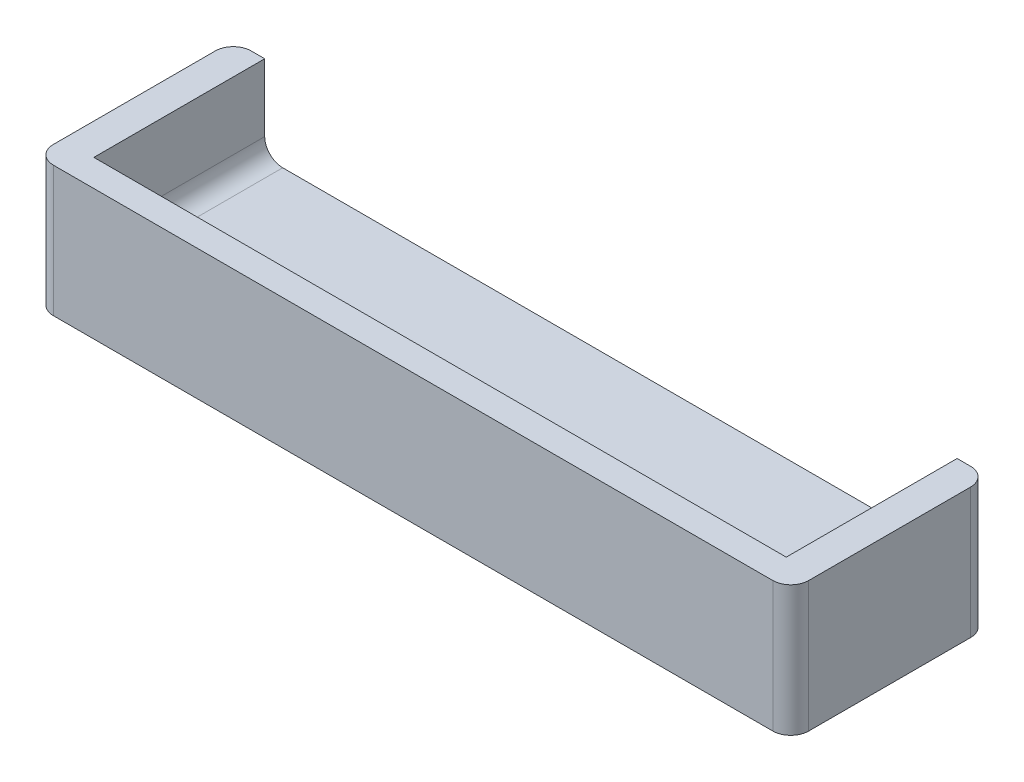
SolidWorks part; units mm, degrees
ref_plane "Alzado" through (0, 0, 0) normal (0, 0, 1) x (1, 0, 0)
ref_plane "Planta" through (0, 0, 0) normal (0, 1, 0) x (1, 0, 0)
ref_plane "Vista lateral" through (0, 0, 0) normal (1, 0, 0) x (0, 0, -1)
sketch "Croquis1" plane through (0, 0, 0) normal (0, 0, 1) x (1, 0, 0)
  line L14 (-38.5, 7.25) -> (-42, 7.25)
  line L21 (42, 7.25) -> (38.5, 7.25)
  line L22 (42, 7.25) -> (42, -7.25)
  line L23 (42, -7.25) -> (-42, -7.25)
  line L24 (-42, 7.25) -> (-42, -7.25)
  line L26 (38.5, 7.25) -> (38.5, -2.25)
  line L27 (38.5, -2.25) -> (-38.5, -2.25)
  line L28 (-38.5, 7.25) -> (-38.5, -2.25)
  point P6 (42, 0)
  point P11 (0, -2.25)
  point P12 (0, -7.25)
  dimension "D4" = 5
  dimension "D1" = 14.5
  dimension "D2" = 77
  dimension "D3" = 3.5
extrude "Saliente-Extruir1" add sketch "Croquis1" along normal blind 14
sketch "Croquis7" plane through (0, 0, 14) normal (0, 0, 1) x (1, 0, 0)
  line L5 (-42, 7.25) -> (42, 7.25)
  line L6 (-42, 7.25) -> (-42, -7.25)
  line L7 (-42, -7.25) -> (42, -7.25)
  line L8 (42, 7.25) -> (42, -7.25)
extrude "Saliente-Extruir6" add sketch "Croquis7" along normal blind 3
sketch "Croquis8" plane through (0, 0, 0) normal (0, 0, -1) x (-1, 0, 0)
  line L14 (-42, 7.25) -> (-42, -7.25)
  line L15 (-42, -7.25) -> (42, -7.25)
  line L16 (42, -7.25) -> (42, 7.25)
  line L17 (42, 7.25) -> (38.5, 7.25)
  line L18 (38.5, 7.25) -> (38.5, -2.25)
  line L19 (38.5, -2.25) -> (-38.5, -2.25)
  line L20 (-38.5, -2.25) -> (-38.5, 7.25)
  line L21 (-38.5, 7.25) -> (-42, 7.25)
  line L22 (-42, 7.25) -> (-42, -7.25)
  line L23 (-42, -7.25) -> (42, -7.25)
  line L24 (42, -7.25) -> (42, 7.25)
  line L25 (42, 7.25) -> (38.5, 7.25)
  line L26 (38.5, 7.25) -> (38.5, -2.25)
  line L27 (38.5, -2.25) -> (-38.5, -2.25)
  line L28 (-38.5, -2.25) -> (-38.5, 7.25)
  line L29 (-38.5, 7.25) -> (-42, 7.25)
  dimension "D1" = 0
extrude "Saliente-Extruir7" add sketch "Croquis8" along normal blind 5
fillet "Redondeo1" radius 2 6 edges at (-42, 0, 17) (42, 0, 17) (-42, 0, -5) (42, 0, -5) (38.5, -2.25, 4.5) (-38.5, -2.25, 4.5)
